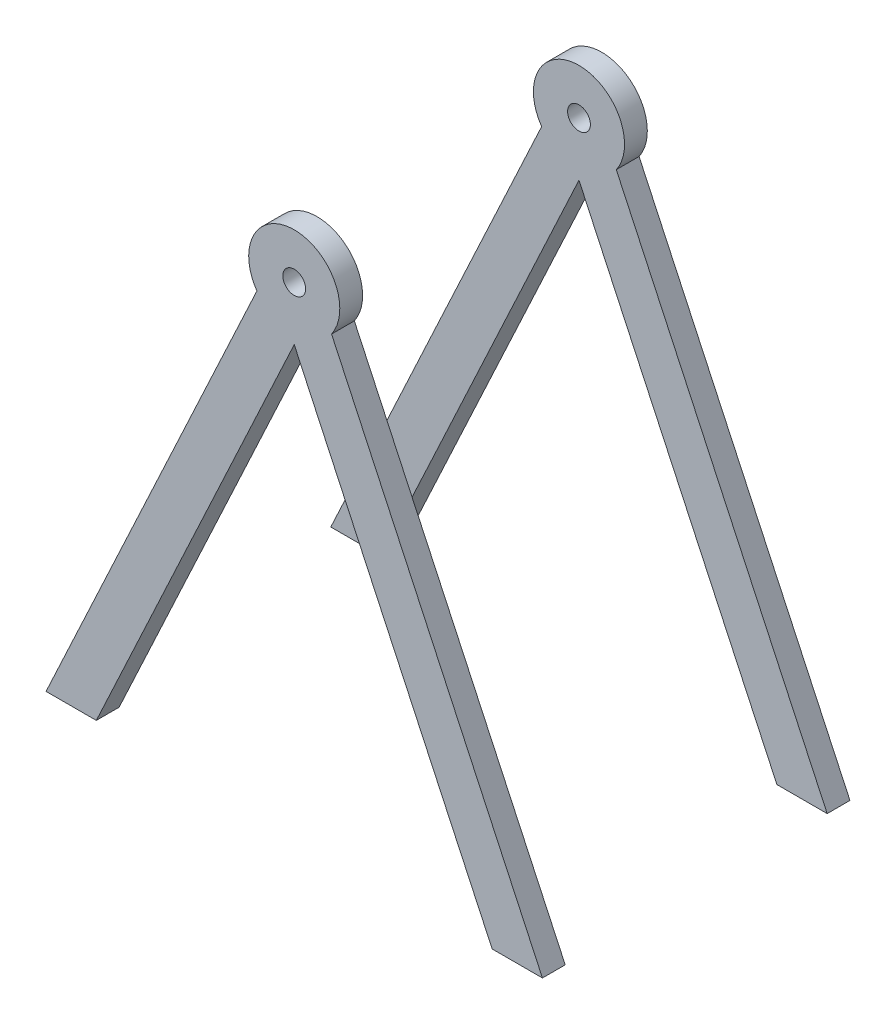
SolidWorks part; units mm, degrees
ref_plane "Front Plane" through (0, 0, 0) normal (0, 0, 1) x (1, 0, 0)
ref_plane "Top Plane" through (0, 0, 0) normal (0, 1, 0) x (1, 0, 0)
ref_plane "Right Plane" through (0, 0, 0) normal (1, 0, 0) x (0, 0, -1)
sketch "Sketch1" plane through (0, 0, 0) normal (0, 0, 1) x (1, 0, 0)
  line L0 (0, 0) -> (0, 210) construction
  line L1 (0, 210) -> (-95.9539, 4.2262) construction
  line L2 (-16.383, 198.5285) -> (-108.9584, 0)
  line L3 (0, 186.338) -> (-86.8908, 0)
  line L4 (-1000, 0) -> (49000, 0) construction
  line L5 (-9.0631, 214.2262) -> (-105.017, 8.4524) construction
  line L6 (-108.9584, 0) -> (-86.8908, 0)
  line L7 (9.0631, 205.7738) -> (-86.8908, 0) construction
  line L8 (108.9584, 0) -> (86.8908, 0)
  line L9 (0, 186.338) -> (86.8908, 0)
  line L10 (16.383, 198.5285) -> (108.9584, 0)
  circle A0 centre (0, 210) radius 5
  arc A2 (16.383, 198.5285) -> (-16.383, 198.5285) centre (0, 210) ccw
  dimension "D2" = 10
  dimension "D3" = 20
  dimension "D1" = 210
  dimension "D4" = 25
  dimension "D5" = 10
  dimension "D6" = 10
extrude "Boss-Extrude1" add sketch "Sketch1" along normal blind 10
ref_plane "Plane1" through (0, 0, -57.5) normal (0, 0, -1) x (-1, 0, 0)
mirror "Mirror2" about plane through (0, 0, -57.5) normal (0, 0, -1) of bodies 101
